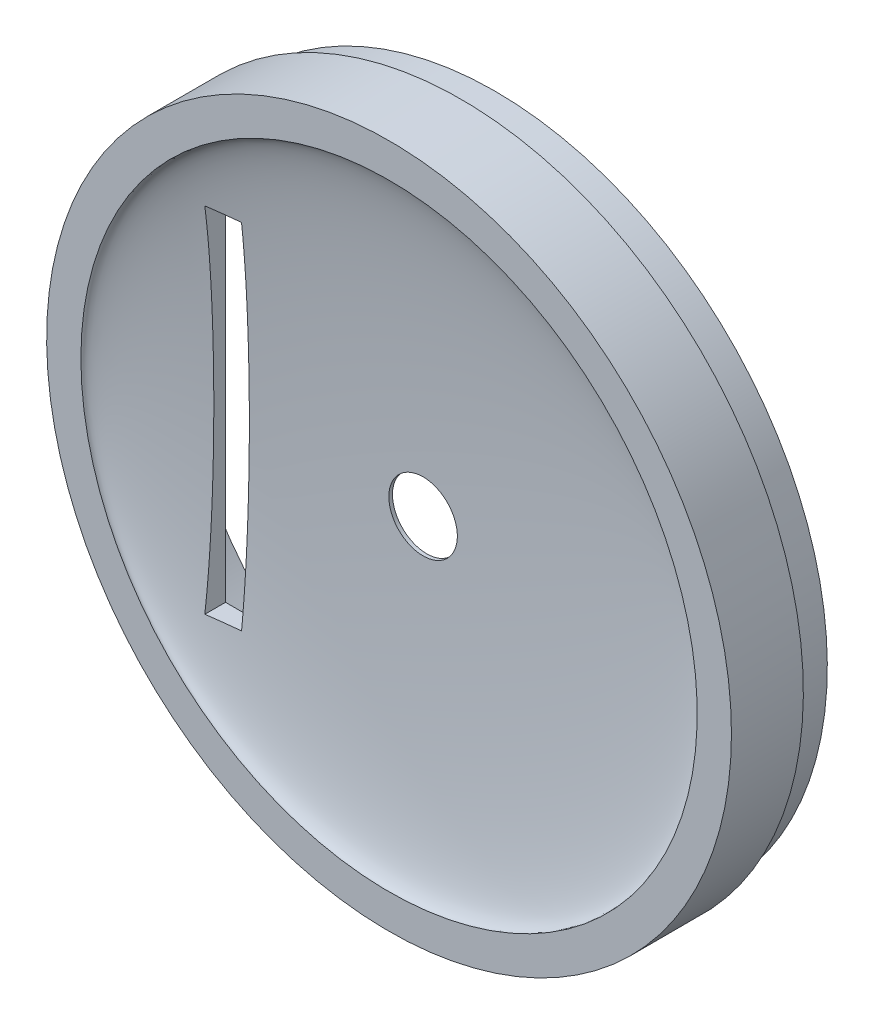
SolidWorks part; units mm, degrees
ref_plane "前视基准面" through (0, 0, 0) normal (0, 0, 1) x (1, 0, 0)
ref_plane "上视基准面" through (0, 0, 0) normal (0, 1, 0) x (1, 0, 0)
ref_plane "右视基准面" through (0, 0, 0) normal (1, 0, 0) x (0, 0, -1)
other "Configuration Table"
sketch "草图1" plane through (0, 0, 0) normal (0, 0, 1) x (1, 0, 0)
  circle A0 centre (0, 0) radius 100
extrude "凸台-拉伸5" add sketch "草图1" along normal blind 10
sketch "草图7" plane through (0, 0, 0) normal (0, 1, 0) x (1, 0, 0)
  line L0 (0, 0) -> (0, -10)
  line L1 (-100, -10) -> (100, -10) construction
  line L2 (0, -10) -> (90, -10)
  line L3 (0, -10) -> (-90, -10)
  ellipse E0 centre (0, -10) end of major axis (90, -10) minor radius 10 (0, 0) -> (-90, -10) ccw
sketch "草图9" plane through (0, 0, 0) normal (0, 0, 1) x (1, 0, 0)
  circle A0 centre (0, 0) radius 100
  point P3 (0, 0)
extrude "凸台-拉伸7" add sketch "草图9" against normal blind 1
revolve "切除-旋转2" cut sketch "草图7" angle 360 about L0
ref_plane "基准面3" through (0, 0, -1) normal (0, 0, -1) x (-1, 0, 0)
sketch "草图11" plane through (0, 0, -1) normal (0, 0, -1) x (-1, 0, 0)
  circle A0 centre (0, 0) radius 100
  circle A1 centre (0, 0) radius 95
extrude "凸台-拉伸8" add sketch "草图11" along normal blind 10
ref_plane "基准面4" through (0, 0, -11) normal (0, 0, -1) x (-1, 0, 0)
sketch "草图12" plane through (0, 0, -11) normal (0, 0, -1) x (-1, 0, 0)
  circle A0 centre (0, 0) radius 95
  circle A1 centre (0, 0) radius 97
extrude "凸台-拉伸9" add sketch "草图12" along normal blind 10
sketch "草图14" plane through (0, 0, -11) normal (0, 0, -1) x (-1, 0, 0)
  line L1 (49.1793, -51.6543) -> (58.7597, -51.6543)
  line L2 (49.1793, -51.6543) -> (49.1793, 51.6543)
  line L3 (49.1793, 51.6543) -> (58.7597, 51.6543)
  line L4 (58.7597, -51.6543) -> (58.7597, 51.6543)
  line L5 (49.1793, -51.6543) -> (58.7597, 51.6543) construction
  line L6 (49.1793, 51.6543) -> (58.7597, -51.6543) construction
  circle A0 centre (0, 0) radius 10
  point P3 (53.9695, 0)
extrude "切除-拉伸4" cut sketch "草图14" against normal blind 20
sketch "草图16" plane through (0, 0, -11) normal (0, 0, -1) x (-1, 0, 0)
  line L0 (0, 0) -> (0, -95)
  circle A0 centre (0, 0) radius 95 construction
ref_plane "基准面5" through (0, -100, 0) normal (0, -1, 0) x (-1, 0, 0)
sketch "草图17" plane through (0, -100, 0) normal (0, -1, 0) x (-1, 0, 0)
  line L0 (0, 11) -> (0, 0)
  line L1 (100, 11) -> (-100, 11) construction
  line L3 (-14.4359, 11) -> (14.4359, 11)
  line L4 (-14.4359, 11) -> (-14.4359, 0)
  line L5 (-14.4359, 0) -> (14.4359, 0)
  line L6 (14.4359, 11) -> (14.4359, 0)
  line L7 (-14.4359, 11) -> (14.4359, 0) construction
  line L8 (-14.4359, 0) -> (14.4359, 11) construction
  point P6 (0, 5.5)
extrude "切除-拉伸5" cut sketch "草图17" against normal blind 20 contours L4 L5 L0 L3 | L6 L3 L0 L5
